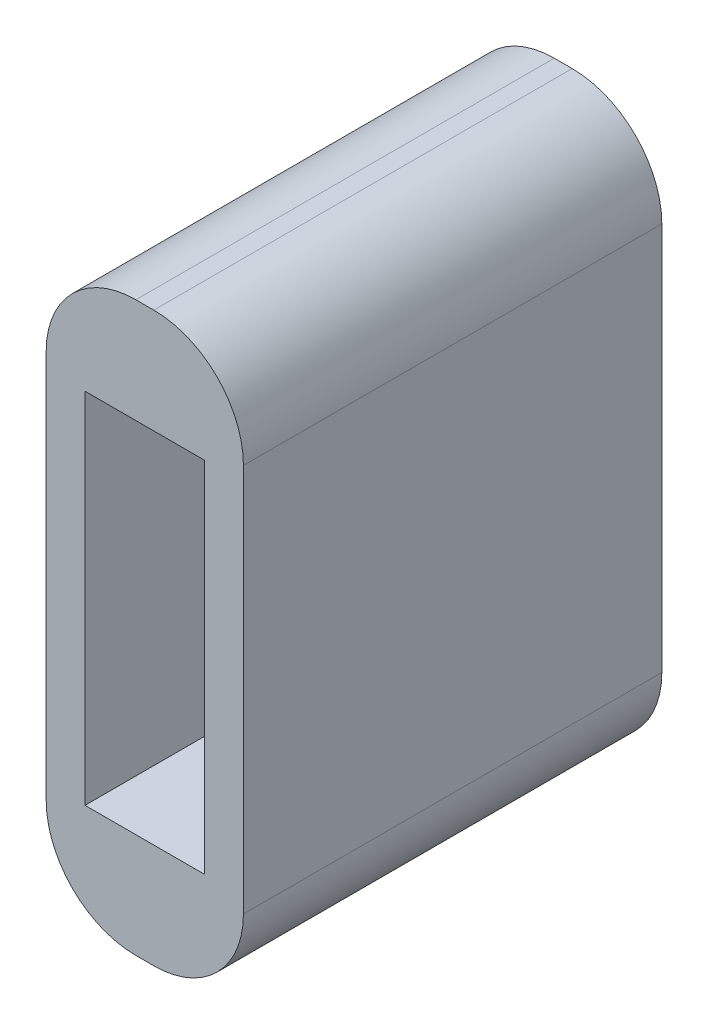
SolidWorks part; units mm, degrees
material "Copper"
ref_plane "Front Plane" through (0, 0, 0) normal (0, 0, 1) x (1, 0, 0)
ref_plane "Top Plane" through (0, 0, 0) normal (0, 1, 0) x (1, 0, 0)
ref_plane "Right Plane" through (0, 0, 0) normal (1, 0, 0) x (0, 0, -1)
sketch "Sketch1" plane through (0, 0, 0) normal (0, 0, 1) x (1, 0, 0)
  line L1 (-1.65, 4.75) -> (1.65, 4.75)
  line L2 (-1.65, 4.75) -> (-1.65, -4.75)
  line L3 (-1.65, -4.75) -> (1.65, -4.75)
  line L4 (1.65, 4.75) -> (1.65, -4.75)
  line L5 (0, -4.75) -> (0, 4.75) construction
  line L6 (-1.65, 0) -> (1.65, 0) construction
  point P0 (0, 0)
  dimension "D1" = 9.5
  dimension "D2" = 3.3
extrude "Boss-Extrude1" add sketch "Sketch1" along normal blind 7
fillet "Fillet1" radius 1.5 4 edges at (1.65, -4.75, 3.5) (-1.65, -4.75, 3.5) (-1.65, 4.75, 3.5) (1.65, 4.75, 3.5)
sketch "Sketch2" plane through (0, 0, 7) normal (0, 0, 1) x (1, 0, 0)
  line L1 (-1, 3) -> (1, 3)
  line L2 (-1, 3) -> (-1, -3)
  line L3 (-1, -3) -> (1, -3)
  line L4 (1, 3) -> (1, -3)
  line L5 (0, -3) -> (0, 3) construction
  line L6 (-1, 0) -> (1, 0) construction
  point P0 (0, 0)
  dimension "D1" = 2
  dimension "D2" = 6
extrude "Cut-Extrude1" cut sketch "Sketch2" against normal blind 7
